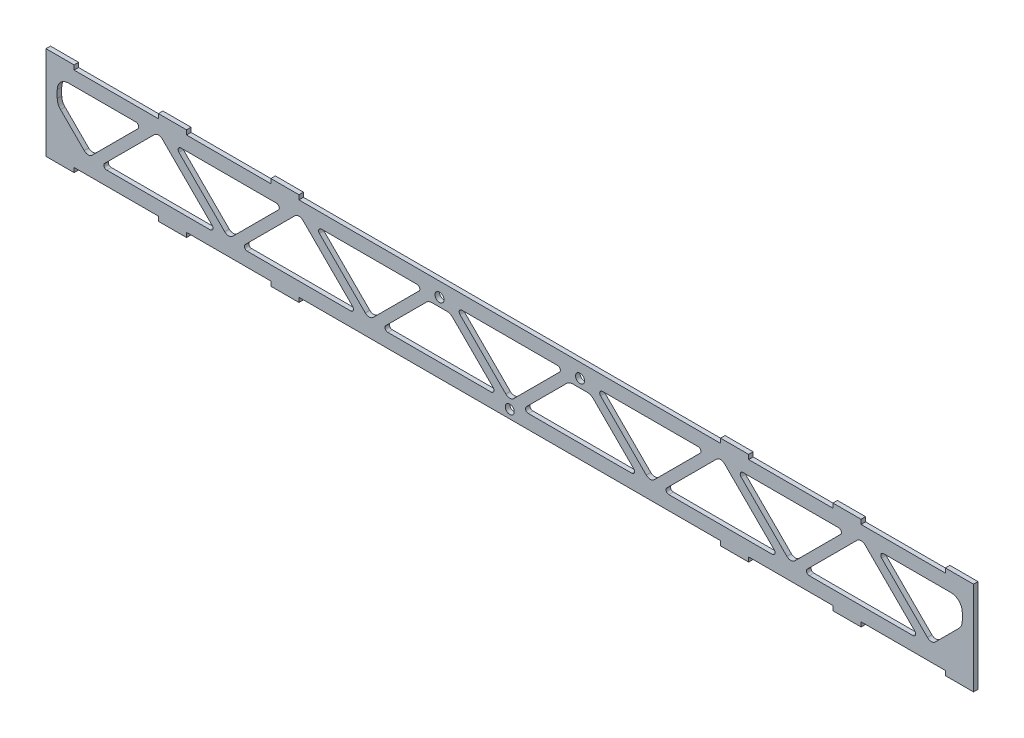
SolidWorks part; units mm, degrees
ref_plane "Front Plane" through (0, 0, 0) normal (0, 0, 1) x (1, 0, 0)
ref_plane "Top Plane" through (0, 0, 0) normal (0, 1, 0) x (1, 0, 0)
ref_plane "Right Plane" through (0, 0, 0) normal (1, 0, 0) x (0, 0, -1)
sketch "Sketch1" plane through (0, 0, 0) normal (0, 0, 1) x (1, 0, 0)
  line L1 (-180, -15) -> (180, -15)
  line L2 (-180, -15) -> (-180, 15)
  line L3 (-180, 15) -> (180, 15)
  line L4 (180, -15) -> (180, 15)
  line L5 (-180, -15) -> (180, 15) construction
  line L6 (-180, 15) -> (180, -15) construction
  point P0 (0, 0)
  dimension "D1" = 360
  dimension "D2" = 30
extrude "Boss-Extrude1" add sketch "Sketch1" along normal blind 1.6
sketch "Sketch2" plane through (0, 0, 1.6) normal (0, 0, 1) x (1, 0, 0)
  line L0 (0, 15) -> (0, -15) construction
  line L1 (180, 15) -> (-180, 15) construction
  line L2 (-180, -15) -> (180, -15) construction
  line L3 (115, 15) -> (125, 15)
  line L4 (75, 15) -> (85, 15)
  line L5 (75, 15) -> (75, 16.6)
  line L6 (75, 16.6) -> (85, 16.6)
  line L7 (85, 15) -> (85, 16.6)
  line L8 (115, 15) -> (115, 16.6)
  line L9 (115, 16.6) -> (125, 16.6)
  line L10 (125, 15) -> (125, 16.6)
  line L11 (155, 15) -> (165, 15)
  line L12 (155, 15) -> (155, 16.6)
  line L13 (155, 16.6) -> (165, 16.6)
  line L14 (165, 15) -> (165, 16.6)
  line L15 (-165, 15) -> (-165, 16.6)
  line L16 (-155, 16.6) -> (-165, 16.6)
  line L17 (-155, 15) -> (-155, 16.6)
  line L18 (-155, 15) -> (-165, 15)
  line L19 (-125, 15) -> (-125, 16.6)
  line L20 (-115, 16.6) -> (-125, 16.6)
  line L21 (-115, 15) -> (-115, 16.6)
  line L22 (-85, 15) -> (-85, 16.6)
  line L23 (-75, 16.6) -> (-85, 16.6)
  line L24 (-75, 15) -> (-75, 16.6)
  line L25 (-75, 15) -> (-85, 15)
  line L26 (-115, 15) -> (-125, 15)
  line L27 (-180, 0) -> (180, 0) construction
  line L28 (-180, 15) -> (-180, -15) construction
  line L29 (180, -15) -> (180, 15) construction
  line L30 (-115, -15) -> (-125, -15)
  line L31 (-75, -15) -> (-85, -15)
  line L32 (-75, -15) -> (-75, -16.6)
  line L33 (-75, -16.6) -> (-85, -16.6)
  line L34 (-85, -15) -> (-85, -16.6)
  line L35 (-115, -15) -> (-115, -16.6)
  line L36 (-115, -16.6) -> (-125, -16.6)
  line L37 (-125, -15) -> (-125, -16.6)
  line L38 (-155, -15) -> (-165, -15)
  line L39 (-155, -15) -> (-155, -16.6)
  line L40 (-155, -16.6) -> (-165, -16.6)
  line L41 (-165, -15) -> (-165, -16.6)
  line L42 (165, -15) -> (165, -16.6)
  line L43 (155, -16.6) -> (165, -16.6)
  line L44 (155, -15) -> (155, -16.6)
  line L45 (155, -15) -> (165, -15)
  line L46 (125, -15) -> (125, -16.6)
  line L47 (115, -16.6) -> (125, -16.6)
  line L48 (115, -15) -> (115, -16.6)
  line L49 (85, -15) -> (85, -16.6)
  line L50 (75, -16.6) -> (85, -16.6)
  line L51 (75, -15) -> (75, -16.6)
  line L52 (75, -15) -> (85, -15)
  line L53 (115, -15) -> (125, -15)
  dimension "D1" = 10
  dimension "D2" = 75
  dimension "D3" = 1.6
  dimension "D5" = 30
  dimension "D4" = 3
extrude "Boss-Extrude2" add sketch "Sketch2" against normal up to surface (1.6 mm away) up to face at (0, 0, 0)
sketch "Sketch3" plane through (0, 0, 1.6) normal (0, 0, 1) x (1, 0, 0)
  line L0 (-167, 10) -> (-133, 10)
  line L1 (-167.7071, 8.2929) -> (-151.4142, -8)
  line L3 (-180, 15) -> (-180, -15) construction
  line L4 (-150, -10) -> (-150, 10) construction
  line L5 (-125, 15) -> (-155, 15) construction
  line L6 (-132.2929, 8.2929) -> (-148.5858, -8)
  line L7 (-117, 10) -> (-83, 10)
  line L8 (-117.7071, 8.2929) -> (-101.4142, -8)
  line L9 (-82.2929, 8.2929) -> (-98.5858, -8)
  line L10 (-100, -10) -> (-100, 10) construction
  line L11 (-67, 10) -> (-33, 10)
  line L12 (-67.7071, 8.2929) -> (-51.4142, -8)
  line L13 (-32.2929, 8.2929) -> (-48.5858, -8)
  line L14 (-50, -10) -> (-50, 10) construction
  line L15 (-17, 10) -> (17, 10)
  line L16 (-17.7071, 8.2929) -> (-1.4142, -8)
  line L17 (17.7071, 8.2929) -> (1.4142, -8)
  line L18 (0, -10) -> (0, 10) construction
  line L19 (33, 10) -> (67, 10)
  line L20 (32.2929, 8.2929) -> (48.5858, -8)
  line L21 (67.7071, 8.2929) -> (51.4142, -8)
  line L22 (50, -10) -> (50, 10) construction
  line L23 (83, 10) -> (117, 10)
  line L24 (82.2929, 8.2929) -> (98.5858, -8)
  line L25 (117.7071, 8.2929) -> (101.4142, -8)
  line L26 (100, -10) -> (100, 10) construction
  line L27 (133, 10) -> (167, 10)
  line L28 (132.2929, 8.2929) -> (148.5858, -8)
  line L29 (167.7071, 8.2929) -> (151.4142, -8)
  line L30 (150, -10) -> (150, 10) construction
  arc A0 (-167, 10) -> (-167.7071, 8.2929) centre (-167, 9) ccw
  arc A1 (-151.4142, -8) -> (-148.5858, -8) centre (-150, -6.5858) ccw
  arc A2 (-133, 10) -> (-132.2929, 8.2929) centre (-133, 9) cw
  arc A3 (-117, 10) -> (-117.7071, 8.2929) centre (-117, 9) ccw
  arc A4 (-101.4142, -8) -> (-98.5858, -8) centre (-100, -6.5858) ccw
  arc A5 (-83, 10) -> (-82.2929, 8.2929) centre (-83, 9) cw
  arc A6 (-67, 10) -> (-67.7071, 8.2929) centre (-67, 9) ccw
  arc A7 (-51.4142, -8) -> (-48.5858, -8) centre (-50, -6.5858) ccw
  arc A8 (-33, 10) -> (-32.2929, 8.2929) centre (-33, 9) cw
  arc A9 (-17, 10) -> (-17.7071, 8.2929) centre (-17, 9) ccw
  arc A10 (-1.4142, -8) -> (1.4142, -8) centre (0, -6.5858) ccw
  arc A11 (17, 10) -> (17.7071, 8.2929) centre (17, 9) cw
  arc A12 (33, 10) -> (32.2929, 8.2929) centre (33, 9) ccw
  arc A13 (48.5858, -8) -> (51.4142, -8) centre (50, -6.5858) ccw
  arc A14 (67, 10) -> (67.7071, 8.2929) centre (67, 9) cw
  arc A15 (83, 10) -> (82.2929, 8.2929) centre (83, 9) ccw
  arc A16 (98.5858, -8) -> (101.4142, -8) centre (100, -6.5858) ccw
  arc A17 (117, 10) -> (117.7071, 8.2929) centre (117, 9) cw
  arc A18 (133, 10) -> (132.2929, 8.2929) centre (133, 9) ccw
  arc A19 (148.5858, -8) -> (151.4142, -8) centre (150, -6.5858) ccw
  arc A20 (167, 10) -> (167.7071, 8.2929) centre (167, 9) cw
  point P2 (-150, 0)
  point P9 (-180, 0)
  point P20 (-100, 0)
  point P34 (-50, 0)
  point P46 (0, 0)
  point P58 (50, 0)
  point P70 (100, 0)
  point P82 (150, 0)
  dimension "D3" = 1
  dimension "D7" = 2
  dimension "D1" = 5
  dimension "D2" = 45
  dimension "D4" = 30
  dimension "D5" = 7
  dimension "D6" = 50
  dimension "D8" = 34
extrude "Cut-Extrude1" cut sketch "Sketch3" against normal through all
sketch "Sketch4" plane through (0, 0, 1.6) normal (0, 0, 1) x (1, 0, 0)
  line L0 (-125, 10) -> (-125, -10) construction
  line L1 (-167, 10) -> (-133, 10) construction
  line L2 (-150, -10) -> (-150, 10) construction
  line L6 (-180, 0) -> (180, 0) construction
  line L7 (180, -15) -> (180, 15) construction
  line L8 (-143.4142, -10) -> (-106.5858, -10)
  line L9 (-105.8787, -8.2929) -> (-123.5858, 9.4142)
  line L10 (-144.1213, -8.2929) -> (-126.4142, 9.4142)
  line L11 (-155, -15) -> (-125, -15) construction
  line L12 (-93.4142, -10) -> (-56.5858, -10)
  line L13 (-55.8787, -8.2929) -> (-73.5858, 9.4142)
  line L14 (-94.1213, -8.2929) -> (-76.4142, 9.4142)
  line L15 (-75, 10) -> (-75, -10) construction
  line L16 (-43.4142, -10) -> (-6.5858, -10)
  line L17 (-5.8787, -8.2929) -> (-23.5858, 9.4142)
  line L18 (-44.1213, -8.2929) -> (-26.4142, 9.4142)
  line L19 (-25, 10) -> (-25, -10) construction
  line L20 (6.5858, -10) -> (43.4142, -10)
  line L21 (44.1213, -8.2929) -> (26.4142, 9.4142)
  line L22 (5.8787, -8.2929) -> (23.5858, 9.4142)
  line L23 (25, 10) -> (25, -10) construction
  line L24 (56.5858, -10) -> (93.4142, -10)
  line L25 (94.1213, -8.2929) -> (76.4142, 9.4142)
  line L26 (55.8787, -8.2929) -> (73.5858, 9.4142)
  line L27 (75, 10) -> (75, -10) construction
  line L28 (106.5858, -10) -> (143.4142, -10)
  line L29 (144.1213, -8.2929) -> (126.4142, 9.4142)
  line L30 (105.8787, -8.2929) -> (123.5858, 9.4142)
  line L31 (125, 10) -> (125, -10) construction
  arc A0 (-76.4142, 9.4142) -> (-73.5858, 9.4142) centre (-75, 8) cw
  arc A1 (-55.8787, -8.2929) -> (-56.5858, -10) centre (-56.5858, -9) cw
  arc A4 (-93.4142, -10) -> (-94.1213, -8.2929) centre (-93.4142, -9) cw
  arc A6 (-126.4142, 9.4142) -> (-123.5858, 9.4142) centre (-125, 8) cw
  arc A7 (-105.8787, -8.2929) -> (-106.5858, -10) centre (-106.5858, -9) cw
  arc A8 (-143.4142, -10) -> (-144.1213, -8.2929) centre (-143.4142, -9) cw
  arc A9 (-26.4142, 9.4142) -> (-23.5858, 9.4142) centre (-25, 8) cw
  arc A10 (-5.8787, -8.2929) -> (-6.5858, -10) centre (-6.5858, -9) cw
  arc A11 (-43.4142, -10) -> (-44.1213, -8.2929) centre (-43.4142, -9) cw
  arc A12 (23.5858, 9.4142) -> (26.4142, 9.4142) centre (25, 8) cw
  arc A13 (44.1213, -8.2929) -> (43.4142, -10) centre (43.4142, -9) cw
  arc A14 (6.5858, -10) -> (5.8787, -8.2929) centre (6.5858, -9) cw
  arc A15 (73.5858, 9.4142) -> (76.4142, 9.4142) centre (75, 8) cw
  arc A16 (94.1213, -8.2929) -> (93.4142, -10) centre (93.4142, -9) cw
  arc A17 (56.5858, -10) -> (55.8787, -8.2929) centre (56.5858, -9) cw
  arc A18 (123.5858, 9.4142) -> (126.4142, 9.4142) centre (125, 8) cw
  arc A19 (144.1213, -8.2929) -> (143.4142, -10) centre (143.4142, -9) cw
  arc A20 (106.5858, -10) -> (105.8787, -8.2929) centre (106.5858, -9) cw
  dimension "D1" = 1
  dimension "D3" = 2
  dimension "D2" = 45
  dimension "D4" = 25
  dimension "D5" = 5
  dimension "D7" = 50
  dimension "D6" = 6
extrude "Cut-Extrude2" cut sketch "Sketch4" against normal through all
sketch "Sketch5" plane through (0, 0, 1.6) normal (0, 0, 1) x (1, 0, 0)
  line L1 (-180, 15) -> (-165, 15)
  line L2 (-180, 15) -> (-180, -15)
  line L3 (-180, -15) -> (-165, -15)
  line L4 (-165, 15) -> (-165, -15)
  line L5 (165, 15) -> (180, 15)
  line L6 (165, 15) -> (165, -15)
  line L7 (165, -15) -> (180, -15)
  line L8 (180, 15) -> (180, -15)
extrude "Cut-Extrude3" cut sketch "Sketch5" against normal through all
sketch "Sketch6" plane through (0, 0, 1.6) normal (0, 0, 1) x (1, 0, 0)
  line L0 (-155, 16.6) -> (-165, 16.6) construction
  line L1 (-165, -16.6) -> (-161, -16.6)
  line L2 (-165, -16.6) -> (-165, 16.6)
  line L3 (-165, 16.6) -> (-161, 16.6)
  line L4 (-161, -16.6) -> (-161, 16.6)
  line L5 (0, 15) -> (0, -15) construction
  line L6 (75, 15) -> (-75, 15) construction
  line L7 (-75, -15) -> (75, -15) construction
  line L8 (161, -16.6) -> (161, 16.6)
  line L9 (165, 16.6) -> (161, 16.6)
  line L10 (165, -16.6) -> (165, 16.6)
  line L11 (165, -16.6) -> (161, -16.6)
  dimension "D1" = 4
extrude "Boss-Extrude3" add sketch "Sketch6" against normal up to surface (1.6 mm away) up to face at (0, 0.626, 0)
fillet "Fillet1" radius 4 4 edges at (161, 1.5858, 0.8) (161, 10, 0.8) (-161, 1.5858, 0.8) (-161, 10, 0.8)
sketch "Sketch7" plane through (0, 0, 1.6) normal (0, 0, 1) x (1, 0, 0)
  line L3 (0, 15) -> (0, -15) construction
  line L4 (75, 15) -> (-75, 15) construction
  line L5 (-75, -15) -> (75, -15) construction
  line L12 (-26.4142, 9.4142) -> (-44.1213, -8.2929) construction
  line L14 (-26.4142, 9.4142) -> (-29.7071, 6.1213)
  line L15 (-27.5858, 7) -> (-22.4142, 7)
  line L16 (-25, 10) -> (-25, 7) construction
  line L17 (-23.5858, 9.4142) -> (-20.2929, 6.1213)
  line L18 (25, 10) -> (25, 7) construction
  line L19 (23.5858, 9.4142) -> (20.2929, 6.1213)
  line L20 (27.5858, 7) -> (22.4142, 7)
  line L21 (26.4142, 9.4142) -> (29.7071, 6.1213)
  arc A0 (-23.5858, 9.4142) -> (-26.4142, 9.4142) centre (-25, 8) ccw construction
  arc A1 (-23.5858, 9.4142) -> (-26.4142, 9.4142) centre (-25, 8) ccw
  arc A2 (-29.7071, 6.1213) -> (-27.5858, 7) centre (-27.5858, 4) cw
  arc A3 (-20.2929, 6.1213) -> (-22.4142, 7) centre (-22.4142, 4) ccw
  arc A4 (20.2929, 6.1213) -> (22.4142, 7) centre (22.4142, 4) cw
  arc A5 (29.7071, 6.1213) -> (27.5858, 7) centre (27.5858, 4) ccw
  arc A6 (23.5858, 9.4142) -> (26.4142, 9.4142) centre (25, 8) cw
  point P0 (-25, 10)
  dimension "D2" = 3
  dimension "D1" = 8
extrude "Boss-Extrude4" add sketch "Sketch7" against normal up to surface (1.6 mm away) up to face at (150.5826, 2.789, 0)
sketch "Sketch8" plane through (0, 0, 1.6) normal (0, 0, 1) x (1, 0, 0)
  line L0 (0, 15) -> (0, -15) construction
  line L1 (75, 15) -> (-75, 15) construction
  line L2 (-75, -15) -> (75, -15) construction
  line L4 (-27.5858, 7) -> (-22.4142, 7) construction
  circle A0 centre (-25, 10) radius 1.6
  circle A1 centre (25, 10) radius 1.6
  circle A2 centre (0, -12) radius 1.6
  point P17 (-25, 7)
  dimension "D1" = 3.2
  dimension "D2" = 5
  dimension "D3" = 3
extrude "Cut-Extrude4" cut sketch "Sketch8" against normal through all
